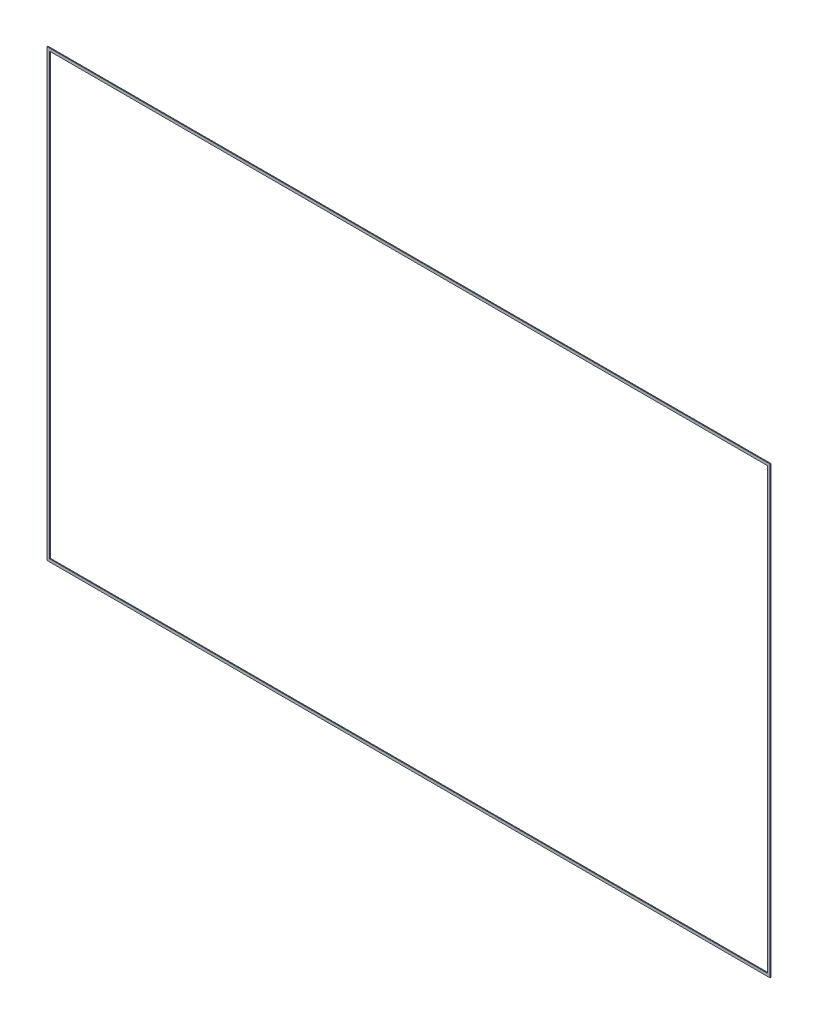
SolidWorks part; units mm, degrees
ref_plane "前视基准面" through (0, 0, 0) normal (0, 0, 1) x (1, 0, 0)
ref_plane "上视基准面" through (0, 0, 0) normal (0, 1, 0) x (1, 0, 0)
ref_plane "右视基准面" through (0, 0, 0) normal (1, 0, 0) x (0, 0, -1)
sketch "草图1" plane through (0, 0, 0) normal (0, 0, 1) x (1, 0, 0)
  line L0 (1, 159) -> (259, 159)
  line L1 (0, 0) -> (260, 0)
  line L2 (0, 0) -> (0, 160)
  line L3 (0, 160) -> (260, 160)
  line L4 (260, 0) -> (260, 160)
  line L5 (259, 1) -> (259, 159)
  line L6 (1, 1) -> (259, 1)
  line L7 (1, 1) -> (1, 159)
  dimension "D1" = 160
  dimension "D2" = 260
  dimension "D3" = 1
extrude "凸台-拉伸2" add sketch "草图1" along normal blind 0.3
